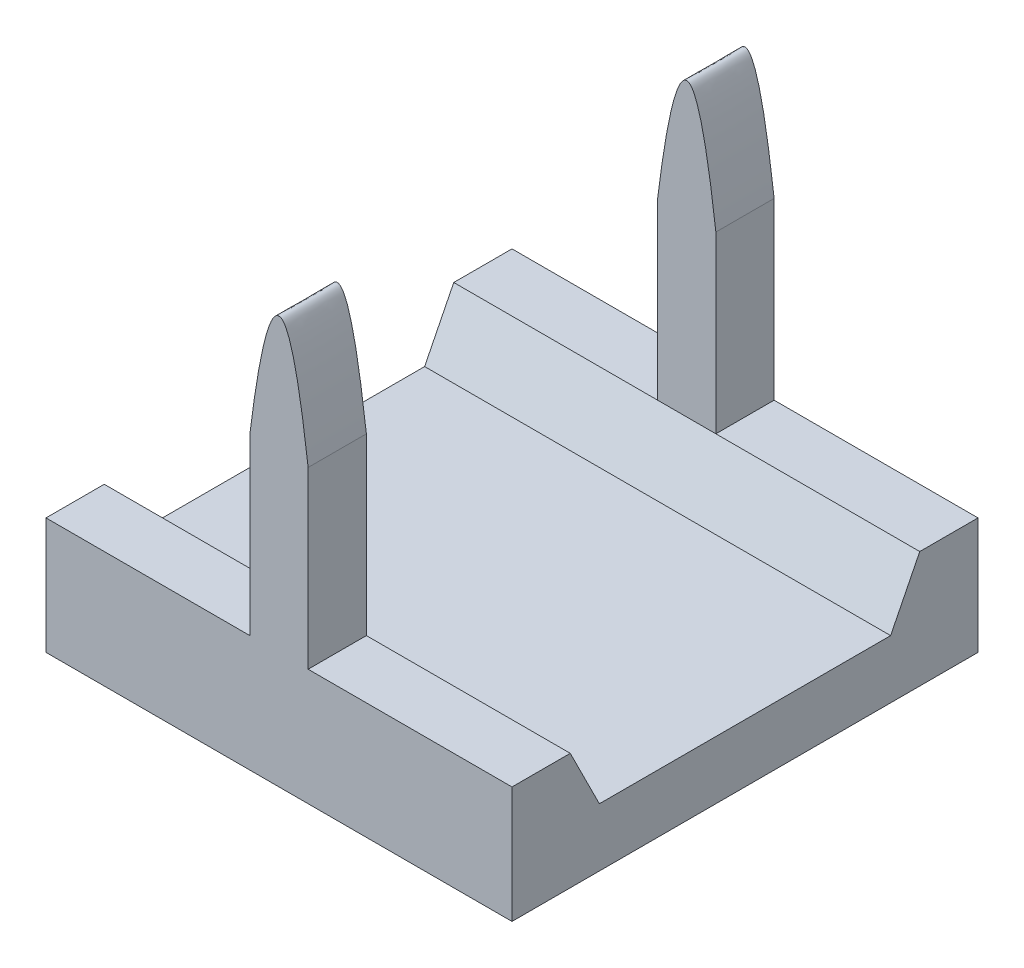
SolidWorks part; units mm, degrees
ref_plane "Front Plane" through (0, 0, 0) normal (0, 0, 1) x (1, 0, 0)
ref_plane "Top Plane" through (0, 0, 0) normal (0, 1, 0) x (1, 0, 0)
ref_plane "Right Plane" through (0, 0, 0) normal (1, 0, 0) x (0, 0, -1)
sketch "Sketch2" plane through (0, 0, 0) normal (0, 1, 0) x (1, 0, 0)
  line L1 (0, 0) -> (80, 0)
  line L2 (0, 0) -> (0, 80)
  line L3 (0, 80) -> (80, 80)
  line L4 (80, 0) -> (80, 80)
  line L5 (0, 0) -> (80, 80) construction
  line L6 (0, 80) -> (80, 0) construction
  point P4 (40, 40)
  dimension "D1" = 80
  dimension "D2" = 80
extrude "Boss-Extrude1" add sketch "Sketch2" along normal blind 20
sketch "Sketch3" plane through (0, 0, 0) normal (0, 0, 1) x (1, 0, 0)
  line L0 (35, 20) -> (35, 50)
  line L1 (0, 20) -> (80, 20) construction
  line L2 (45, 20) -> (45, 50)
  line L3 (0, 20) -> (0, 0) construction
  line L5 (35, 20) -> (45, 20)
  spline S0 degree 2 poles (35, 50) (40, 90) (45, 50) knots 0 0 0 1 1 1
  point P8 (0, 0)
  point P9 (38.6679, 60.3324)
  dimension "D1" = 10
  dimension "D2" = 35
  dimension "D3" = 5
  dimension "D4" = 30
  dimension "D5" = 20
extrude "Boss-Extrude2" add sketch "Sketch3" against normal blind 10
ref_plane "Plane1" through (0, 0, -40) normal (0, 0, 1) x (1, 0, 0)
mirror "Mirror1" about plane through (0, 0, -40) normal (0, 0, 1) of "Boss-Extrude2"
sketch "Sketch4" plane through (80, 0, 0) normal (1, 0, 0) x (0, 0, -1)
  line L0 (10, 20) -> (15, 10)
  line L1 (0, 20) -> (80, 20) construction
  line L2 (15, 10) -> (65, 10)
  line L3 (65, 10) -> (70, 20)
  line L4 (0, 20) -> (0, 0) construction
  dimension "D1" = 10
  dimension "D2" = 10
  dimension "D3" = 50
  dimension "D4" = 10
  dimension "D5" = 5
extrude "Cut-Extrude1" cut sketch "Sketch4" against normal through all and the other way through all
